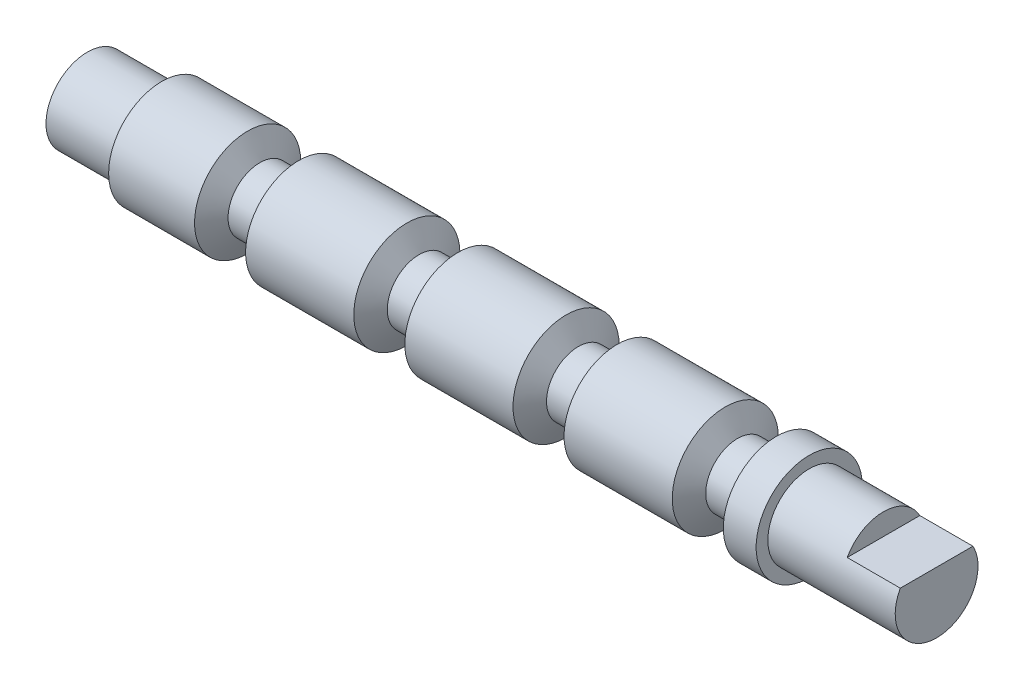
SolidWorks part; units mm, degrees
ref_plane "Front Plane" through (0, 0, 0) normal (0, 0, 1) x (1, 0, 0)
ref_plane "Top Plane" through (0, 0, 0) normal (0, 1, 0) x (1, 0, 0)
ref_plane "Right Plane" through (0, 0, 0) normal (1, 0, 0) x (0, 0, -1)
sketch "Sketch2" plane through (0, 0, 0) normal (0, 1, 0) x (1, 0, 0)
  line L1 (40, -5) -> (-40, -5)
  line L5 (-30.0491, 0) -> (-24.9047, 0)
  line L6 (-5.0953, 0) -> (-6.25, -2)
  line L7 (-6.25, -2) -> (-8.75, -2)
  line L8 (-8.75, -2) -> (-9.9047, 0)
  line L9 (-20.0953, 0) -> (-21.25, -2)
  line L10 (-21.25, -2) -> (-23.75, -2)
  line L11 (-23.75, -2) -> (-24.9047, 0)
  line L21 (-5.0953, 0) -> (5.0953, 0)
  line L22 (-20.0953, 0) -> (-9.9047, 0)
  line L25 (-30.0491, 0) -> (-40, 0)
  line L30 (-40, 0) -> (-40, -5)
  line L31 (0, 0) -> (0, -5) construction
  line L32 (40, 0) -> (40, -5)
  line L33 (30.0491, 0) -> (40, 0)
  line L34 (20.0953, 0) -> (9.9047, 0)
  line L35 (23.75, -2) -> (24.9047, 0)
  line L36 (21.25, -2) -> (23.75, -2)
  line L37 (20.0953, 0) -> (21.25, -2)
  line L38 (8.75, -2) -> (9.9047, 0)
  line L39 (6.25, -2) -> (8.75, -2)
  line L40 (5.0953, 0) -> (6.25, -2)
  line L41 (30.0491, 0) -> (24.9047, 0)
  point P2 (-7.5, -2)
  point P6 (-22.5, -2)
  dimension "D2" = 5
  dimension "D3" = 3
  dimension "D4" = 120
  dimension "D5" = 120
  dimension "D6" = 7.5
  dimension "D7" = 2.5
  dimension "D8" = 22.5
  dimension "D9" = 120
  dimension "D10" = 120
  dimension "D11" = 2.5
  dimension "D12" = 40
revolve "Revolve1" add sketch "Sketch2" angle 360 about L1
sketch "Sketch3" plane through (40, 0, 0) normal (1, 0, 0) x (0, 0, -1)
  circle A0 centre (-5, 0) radius 3.9
  circle A2 centre (-5, 0) radius 5
  circle A3 centre (-5, 0) radius 5
  dimension "D2" = 0
  dimension "D1" = 7.8
sketch "Sketch4" plane through (-40, 0, 0) normal (-1, 0, 0) x (0, 0, 1)
  circle A0 centre (5, 0) radius 3.9
  circle A2 centre (5, 0) radius 5
  circle A3 centre (5, 0) radius 5
  dimension "D1" = 7.8
  dimension "D2" = 0
extrude "Cut-Extrude2" cut sketch "Sketch4" against normal blind 7
extrude "Cut-Extrude4" cut sketch "Sketch3" against normal blind 12
sketch "Sketch5" plane through (40, 0, 0) normal (1, 0, 0) x (0, 0, -1)
  line L0 (-8.422, 1.8709) -> (-1.578, 1.8709)
  line L1 (0, 0) -> (-5, 0) construction
  circle A1 centre (-5, 0) radius 3.9
  arc A2 (-1.578, 1.8709) -> (-8.422, 1.8709) centre (-5, 0) ccw
  dimension "D2" = 1.8709
  dimension "D1" = 0
extrude "Cut-Extrude5" cut sketch "Sketch5" against normal blind 5
